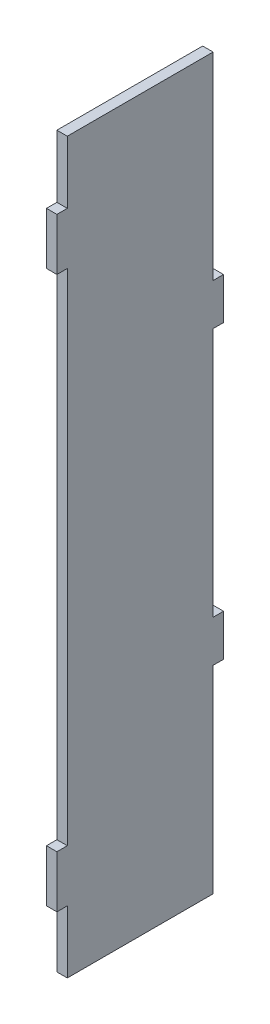
SolidWorks part; units mm, degrees
ref_plane "Front Plane" through (0, 0, 0) normal (0, 0, 1) x (1, 0, 0)
ref_plane "Top Plane" through (0, 0, 0) normal (0, 1, 0) x (1, 0, 0)
ref_plane "Right Plane" through (0, 0, 0) normal (1, 0, 0) x (0, 0, -1)
sketch "Sketch1" plane through (0, 0, 0) normal (1, 0, 0) x (0, 0, -1)
  line L0 (-61.6048, 16.3824) -> (-61.6048, -8.6176)
  line L1 (-56.6048, 311.3824) -> (13.3952, 311.3824)
  line L2 (-56.6048, 311.3824) -> (-56.6048, 281.3824)
  line L3 (-56.6048, -38.6176) -> (13.3952, -38.6176)
  line L4 (-56.6048, 256.3824) -> (-56.6048, 16.3824)
  line L5 (-56.6048, -8.6176) -> (-56.6048, -38.6176)
  line L6 (13.3952, 311.3824) -> (13.3952, 216.3824)
  line L7 (-56.6048, 281.3824) -> (-61.6048, 281.3824)
  line L8 (-61.6048, 281.3824) -> (-61.6048, 256.3824)
  line L9 (-61.6048, 256.3824) -> (-56.6048, 256.3824)
  line L10 (-61.6048, -8.6176) -> (-56.6048, -8.6176)
  line L11 (-56.6048, 16.3824) -> (-61.6048, 16.3824)
  line L13 (13.3952, 76.3824) -> (18.3952, 76.3824)
  line L14 (13.3952, 196.3824) -> (13.3952, 76.3824)
  line L15 (13.3952, 56.3824) -> (13.3952, -38.6176)
  line L17 (13.3952, 216.3824) -> (18.3952, 216.3824)
  line L18 (18.3952, 216.3824) -> (18.3952, 196.3824)
  line L19 (18.3952, 196.3824) -> (13.3952, 196.3824)
  line L20 (18.3952, 76.3824) -> (18.3952, 56.3824)
  line L21 (18.3952, 56.3824) -> (13.3952, 56.3824)
  dimension "D1" = 350
  dimension "D2" = 30
  dimension "D3" = 25
  dimension "D4" = 30
  dimension "D5" = 25
  dimension "D6" = 5
  dimension "D7" = 20
  dimension "D8" = 20
  dimension "D9" = 95
  dimension "D10" = 95
  dimension "D11" = 70
  dimension "D12" = 5
extrude "Boss-Extrude1" add sketch "Sketch1" along normal blind 5
